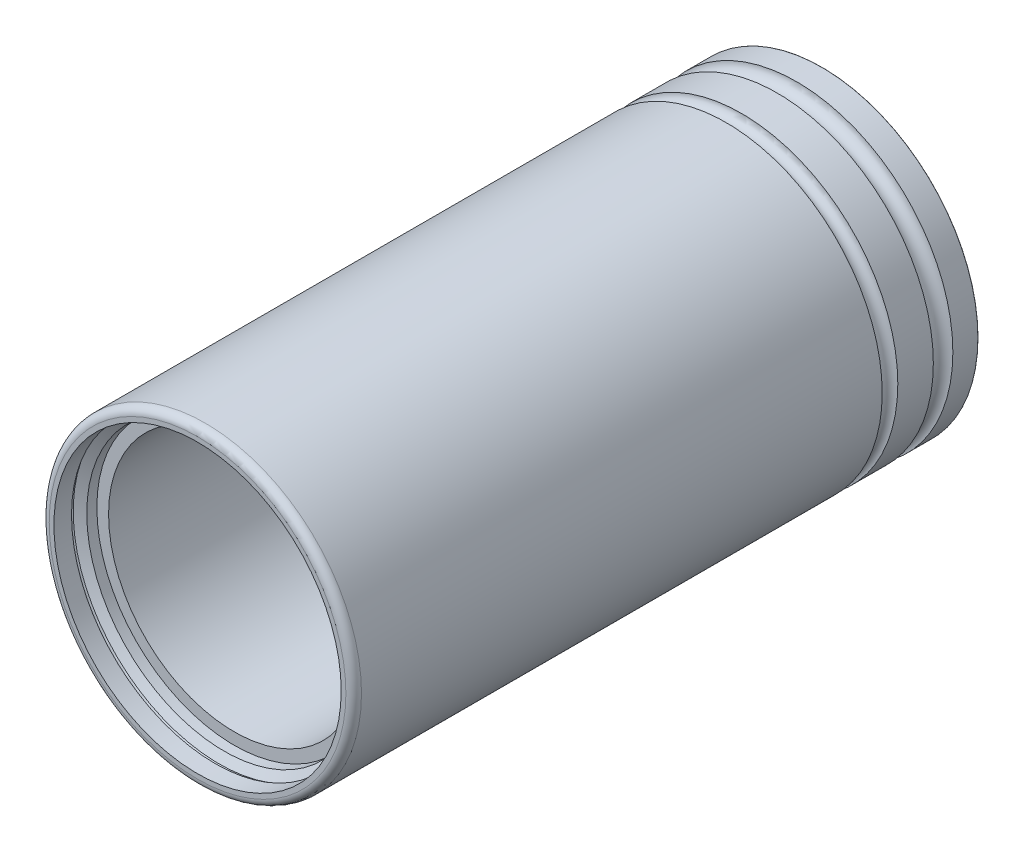
SolidWorks part; units mm, degrees
material "AISI 304"
ref_plane "Спереди" through (0, 0, 0) normal (0, 0, 1) x (1, 0, 0)
ref_plane "Сверху" through (0, 0, 0) normal (0, 1, 0) x (1, 0, 0)
ref_plane "Справа" through (0, 0, 0) normal (1, 0, 0) x (0, 0, -1)
sketch "Эскиз1" plane through (0, 0, 0) normal (0, 0, 1) x (1, 0, 0)
  circle A0 centre (0, 0) radius 20
  dimension "D1" = 40
extrude "Бобышка-Вытянуть1" add sketch "Эскиз1" against normal blind 80
sketch "Эскиз4" plane through (0, 0, 0) normal (1, 0, 0) x (0, 0, -1)
  line L0 (0, 0) -> (0, 17.6)
  line L1 (0, 20) -> (0, -20) construction
  line L2 (0, 17.6) -> (4.7, 17.6)
  line L3 (4.7, 17.6) -> (4.7, 16.1)
  line L4 (4.7, 16.1) -> (27, 16.1)
  line L8 (27, 16.1) -> (27, 17.1)
  line L9 (27, 17.1) -> (28.4, 17.1)
  line L14 (55, 6) -> (57, 6)
  line L15 (57, 6) -> (57, 9.5)
  line L16 (57, 9.5) -> (60.8, 9.5)
  line L20 (62, 9.5) -> (63.5, 9.5)
  line L21 (63.5, 9.5) -> (63.5, 10.75)
  line L22 (63.5, 10.75) -> (75, 10.75)
  line L23 (75, 10.75) -> (75, 12.4)
  line L24 (75, 12.4) -> (78, 12.4)
  line L25 (78, 12.4) -> (78, 10.75)
  line L26 (78, 10.75) -> (80, 10.75)
  line L27 (80, -20) -> (80, 20) construction
  line L28 (80, 10.75) -> (80, 0)
  line L29 (80, 0) -> (0, 0)
  line L52 (55, 6) -> (55, 16.2)
  line L53 (28.4, 17.1) -> (28.9196, 16.2)
  line L54 (28.9196, 16.2) -> (29.8, 16.2)
  line L55 (29.8, 16.2) -> (29.8, 17.7)
  line L56 (29.8, 17.7) -> (33.8, 17.7)
  line L57 (33.8, 17.7) -> (33.8, 16.2)
  line L58 (33.8, 16.2) -> (34.8, 16.2)
  line L59 (34.8, 16.2) -> (34.8, 17.9)
  line L60 (34.8, 17.9) -> (38, 17.9)
  line L61 (38, 17.9) -> (38, 16.2)
  line L62 (38, 16.2) -> (39, 16.2)
  line L63 (39, 16.2) -> (39, 17.7)
  line L64 (39, 17.7) -> (47.8, 17.7)
  line L65 (47.8, 17.7) -> (47.8, 16.2)
  line L66 (47.8, 16.2) -> (48.8, 16.2)
  line L67 (48.8, 16.2) -> (48.8, 17.9)
  line L68 (48.8, 17.9) -> (52, 17.9)
  line L69 (52, 17.9) -> (52, 16.2)
  line L70 (52, 16.2) -> (55, 16.2)
  arc A0 (60.8, 9.5) -> (62, 9.5) centre (61.4, 9.5) cw
  dimension "D8" = 0.6
  dimension "D1" = 10.75
  dimension "D2" = 12.4
  dimension "D3" = 2
  dimension "D4" = 3
  dimension "D5" = 16.5
  dimension "D6" = 2.1
  dimension "D7" = 9.5
  dimension "D9" = 17.1
  dimension "D10" = 2
  dimension "D11" = 60
  dimension "D12" = 17.6
  dimension "D13" = 16.2
  dimension "D14" = 4.7
  dimension "D15" = 29.8
  dimension "D16" = 4
  dimension "D17" = 16.1
  dimension "D18" = 6
  dimension "D19" = 1.4
  dimension "D20" = 23
  dimension "D21" = 27
  dimension "D22" = 17.7
  dimension "D23" = 5.2
  dimension "D24" = 8.8
  dimension "D25" = 34.8
  dimension "D26" = 3.2
  dimension "D27" = 10.8
  dimension "D28" = 3.2
  dimension "D29" = 17.9
revolve "Вырез-Повернуть1" cut sketch "Эскиз4" angle 360 about L29
sketch "Эскиз5" plane through (0, 0, 0) normal (1, 0, 0) x (0, 0, -1)
  line L0 (3.4083, 17.6) -> (1.7917, 17.6)
  line L1 (1.7917, 17.6) -> (2.6, 19)
  line L2 (2.6, 19) -> (3.4083, 17.6)
  line L3 (4.7, 17.6) -> (4.7, -17.6) construction
  line L4 (4.7, 17.6) -> (4.7, -17.6) construction
  line L5 (0, 17.6) -> (0, -17.6) construction
  line L6 (0, 0) -> (8.2655, 0) construction
  line L7 (0, 20) -> (0, -20) construction
  line L8 (0, 20) -> (0, -20) construction
  point P3 (2.6, 17.6)
  dimension "D1" = 1
  dimension "D2" = 60
  dimension "D3" = 2.6
revolve "Вырез-Повернуть2" cut sketch "Эскиз5" angle 360 about L6
fillet "Скругление2" radius 1 1 edges at (20, 0, 0)
sketch "Эскиз6" plane through (0, 0, 0) normal (0, 0, 1) x (1, 0, 0)
  circle A2 centre (0, 0) radius 18.4
  dimension "D1" = 36.8
extrude "Вырез-Вытянуть1" cut sketch "Эскиз6" against normal blind 2.6
fillet "Скругление3" radius 0.05 3 edges at (-10.75, 0, -80) (20, 0, -80) (-6, 0, -57)
fillet "Скругление4" [suppressed] radius 0.1
fillet "Скругление5" [suppressed] radius 0.2
fillet "Скругление6" [suppressed] radius 0.4
fillet "Скругление7" [suppressed] radius 0.2
sketch "Эскиз7" plane through (0, 0, 0) normal (0, 1, 0) x (1, 0, 0)
  line L0 (19.95, 80) -> (-19.95, 80) construction
  line L2 (0, 88.9589) -> (0, 57.4428) construction
  line L3 (-14.5, 80) -> (-15.9559, 80)
  line L8 (-15.9559, 80) -> (-15.9559, 80.8967)
  line L9 (-14.9559, 81.8967) -> (-14.0542, 81.8967)
  line L10 (-13.0542, 80.8967) -> (-13.0542, 80)
  line L11 (-14.5, 80) -> (-13.0542, 80)
  arc A1 (-13.0542, 80.8967) -> (-14.0542, 81.8967) centre (-14.0542, 80.8967) ccw
  arc A2 (-14.9559, 81.8967) -> (-15.9559, 80.8967) centre (-14.9559, 80.8967) ccw
  dimension "D3" = 1
  dimension "D2" = 14.5
revolve "Повернуть1" add sketch "Эскиз7" angle 360 about L2
sketch "Эскиз8" plane through (0, 0, 0) normal (1, 0, 0) x (0, 0, -1)
  line L0 (1, -20) -> (1, 20) construction
  line L1 (1, -20) -> (1, 20) construction
  line L2 (75.5, 20) -> (40.6285, 20) construction
  line L7 (0, 0) -> (74.6339, 0) construction
  line L8 (80, -19.95) -> (80, 19.95) construction
  line L9 (80, -19.95) -> (80, 19.95) construction
  line L10 (79.95, 20) -> (1, 20) construction
  circle A0 centre (75.5, 20) radius 1.25
  circle A1 centre (68.7, 20) radius 1
  dimension "D1" = 2.5
  dimension "D3" = 2
  dimension "D4" = 6.8
  dimension "D2" = 4.5
  dimension "D5" = 20
revolve "Вырез-Повернуть3" cut sketch "Эскиз8" angle 360 about L7
fillet "Скругление10" [suppressed] radius 0.2
fillet "Скругление11" [suppressed] radius 0.2
fillet "Скругление12" radius 0.4 4 edges at (-17.9, 0, -52) (-17.9, 0, -48.8) (-17.9, 0, -38) (-17.9, 0, -34.8)
fillet "Скругление13" radius 0.2 4 edges at (-16.2, 0, -52) (-16.2, 0, -48.8) (-16.2, 0, -38) (-16.2, 0, -34.8)
fillet "Скругление14" radius 0.2 2 edges at (-10.75, 0, -75) (-10.75, 0, -78)
fillet "Скругление15" radius 0.4 2 edges at (-12.4, 0, -78) (-12.4, 0, -75)
fillet "Скругление16" radius 0.2 1 edges at (19, 0, -2.6)
